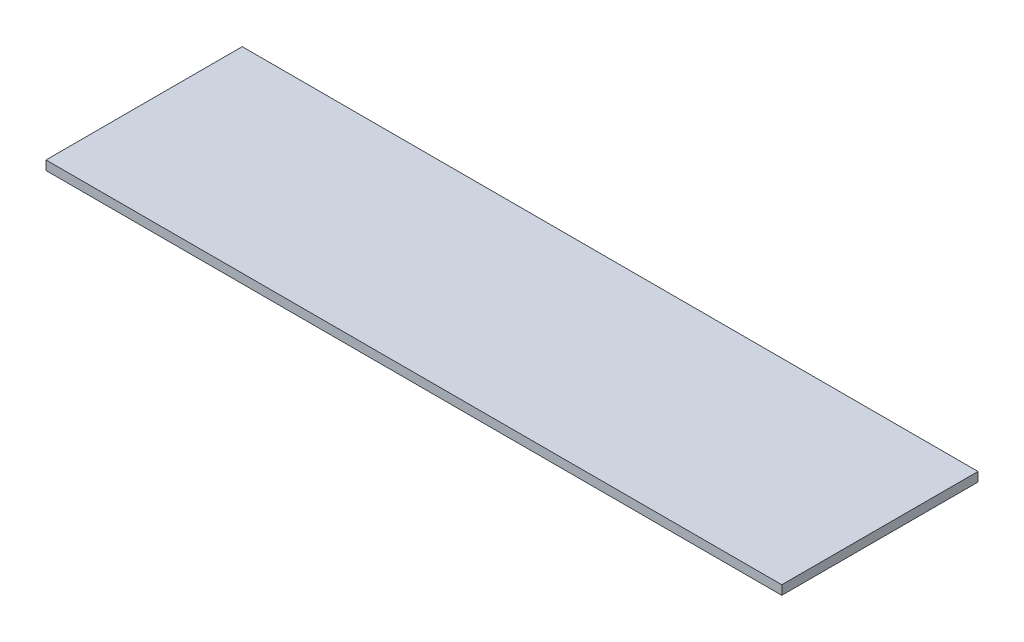
SolidWorks part; units mm, degrees
ref_plane "Front Plane" through (0, 0, 0) normal (0, 0, 1) x (1, 0, 0)
ref_plane "Top Plane" through (0, 0, 0) normal (0, 1, 0) x (1, 0, 0)
ref_plane "Right Plane" through (0, 0, 0) normal (1, 0, 0) x (0, 0, -1)
sketch "Sketch1" plane through (0, 0, 0) normal (0, 1, 0) x (1, 0, 0)
  line L1 (0, 0) -> (381, 0)
  line L2 (0, 0) -> (0, 101.6)
  line L3 (0, 101.6) -> (381, 101.6)
  line L4 (381, 0) -> (381, 101.6)
  dimension "D1" = 101.6
  dimension "D2" = 381
extrude "Boss-Extrude1" add sketch "Sketch1" along normal blind 4.7625
